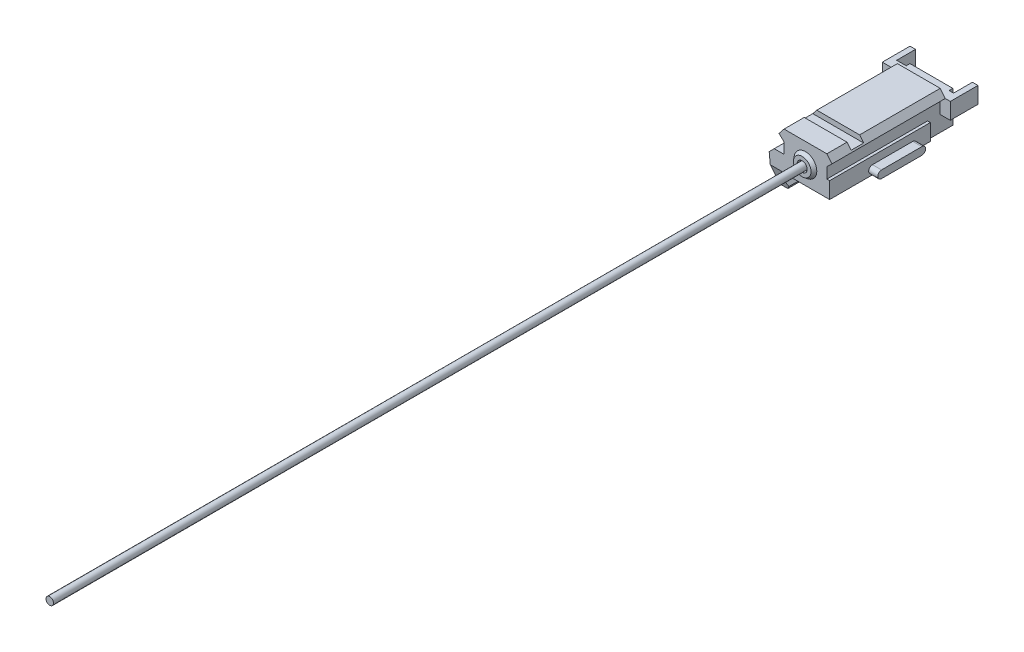
SolidWorks part; units mm, degrees
ref_plane "Plan de face" through (0, 0, 0) normal (0, 0, 1) x (1, 0, 0)
ref_plane "Plan de dessus" through (0, 0, 0) normal (0, 1, 0) x (1, 0, 0)
ref_plane "Plan de droite" through (0, 0, 0) normal (1, 0, 0) x (0, 0, -1)
sketch "Esquisse1" plane through (0, 0, 0) normal (0, 0, 1) x (1, 0, 0)
  line L0 (0, -2) -> (2, 0)
  line L1 (2, 0) -> (4.8, 0)
  line L3 (1.23, -14) -> (4.43, -14)
  line L4 (4.8, 0) -> (4.8, -10.6)
  line L6 (4.43, -11) -> (5.42, -12.5)
  line L7 (5.42, -12.5) -> (4.43, -14)
  line L8 (0, -2) -> (1.23, -14)
  line L9 (4.43, -11) -> (4.8, -10.6)
  point P0 (0, 0)
  dimension "D1" = 4.8
  dimension "D2" = 3.2
  dimension "D6" = 12
  dimension "D5" = 2
  dimension "D3" = 4.19
  dimension "D4" = 2.8
  dimension "D7" = 1.5
  dimension "D8" = 3
  dimension "D9" = 10.6
extrude "Boss.-Extru.1" add sketch "Esquisse1" along normal blind 40
sketch "Esquisse2" plane through (4.8, 0, 0) normal (1, 0, 0) x (0, 0, -1)
  line L1 (-37, -14) -> (-40, -6.3)
  line L2 (-40, -6.3) -> (-40, -14)
  line L3 (-40, -14) -> (0, -14) construction
  line L4 (-40, -14) -> (-37, -14)
  line L5 (-40, 0) -> (0, 0) construction
  line L6 (-40, -10.6) -> (-40, 0) construction
  dimension "D1" = 6.3
  dimension "D2" = 3
extrude "Enlèv. mat.-Extru.1" cut sketch "Esquisse2" against normal through all and the other way through all
ref_plane "Plan1" through (0, -6.5, 0) normal (0, 1, 0) x (-1, 0, 0)
sketch "Esquisse3" plane through (0, -6.5, 0) normal (0, 1, 0) x (-1, 0, 0)
  line L1 (-5.7068, 0) -> (-1.3, 0)
  line L2 (-4.8, 0) -> (-2, 0) construction
  line L3 (-5.7068, 0) -> (-5.7068, 3.75)
  line L4 (-1.3, 0) -> (-4.8, 3.75)
  line L5 (-4.8, 3.75) -> (-5.7068, 3.75)
  line L6 (-4.8, 40) -> (-4.8, 0) construction
  dimension "D1" = 3.5
  dimension "D2" = 3.75
extrude "Enlèv. mat.-Extru.3" cut sketch "Esquisse3" against normal blind 40
ref_plane "Plan2" through (-0.2, 0, 0) normal (1, 0, 0) x (0, 0, -1)
hole_wizard "Chambrage pour vis à tête hexagonale M31" positions "Esquisse5" profile "Esquisse4" counterbore size "M3" standard "ISO" end condition through all
sketch "Esquisse5" plane through (-0.2, 2.2587, 74.5722) normal (1, 0, 0) x (0, 0, -1)
  line L1 (34.5722, -2.2587) -> (74.5722, -2.2587) construction
  line L2 (34.5722, -8.5587) -> (34.5722, -2.2587) construction
  point P0 (55.5722, -11.2587)
  point P1 (45.5722, -11.2587)
  dimension "D1" = 10
  dimension "D2" = 11
  dimension "D3" = 9
sketch "Esquisse4" plane through (-0.2, -9, 19) normal (0, 1, 0) x (0, 0, 1)
  line L0 (0, 0) -> (0, 5.62)
  line L1 (0, 5.62) -> (1.7, 5.62)
  line L3 (1.7, 5.62) -> (1.7, 3)
  line L4 (1.7, 3) -> (2.1, 3)
  line L5 (2.1, 3) -> (2.1, 0)
  line L7 (2.1, 0) -> (0, 0)
  line L11 (0, -6.35) -> (0, 107.95) construction
  dimension "Diamètre du perçage jusqu'au prochain" = 3.4
  dimension "Profondeur du perçage jusqu'au prochain" = 5.62
  dimension "Diamètre du chambrage" = 4.2
  dimension "Profondeur du chambrage" = 3
sketch "Esquisse6" plane through (0.6948, 0, -0.6485) normal (0.7311, 0, -0.6823) x (-0.6823, 0, -0.7311)
  line L1 (-10.1213, -7.9507) -> (-3.0712, -7.9507)
  line L2 (-10.1213, -7.9507) -> (-10.1213, -15.3098)
  line L3 (-10.1213, -15.3098) -> (-3.0712, -15.3098)
  line L4 (-3.0712, -7.9507) -> (-3.0712, -15.3098)
extrude "Enlèv. mat.-Extru.4" cut sketch "Esquisse6" along normal blind 10
ref_plane "Plan3" through (14.4, 0, 0) normal (1, 0, 0) x (0, 0, -1)
sketch "Esquisse7" plane through (0, 0, 40) normal (0, 0, 1) x (1, 0, 0)
  line L0 (4.8, -6.3) -> (4.8, 0) construction
  line L1 (4.8, -6.5) -> (24, -6.5)
  line L2 (4.8, -6.5) -> (4.8, 0)
  line L3 (5.9, 8.7) -> (22.9, 8.7)
  line L4 (22.9, 0) -> (24, 0)
  line L5 (1.23, -14) -> (4.43, -14) construction
  line L6 (5.9, 8.7) -> (3.9, 6.2)
  line L7 (3.9, 6.2) -> (5.9, 4.3)
  line L8 (5.9, 4.3) -> (5.9, 0)
  line L9 (5.9, 0) -> (4.8, 0)
  line L10 (4.8, 0) -> (2, 0) construction
  line L12 (14.4, -8.9588) -> (14.4, 10.2832) construction
  line L13 (14.4, -11.5346) -> (14.4, 11.5346) construction
  line L14 (22.9, 4.3) -> (22.9, 0)
  line L15 (24.9, 6.2) -> (22.9, 4.3)
  line L16 (22.9, 8.7) -> (24.9, 6.2)
  line L17 (24, -6.5) -> (24, 0)
  point P25 (14.4, 8.7)
  point P26 (14.4, -6.5)
  dimension "D1" = 7.5
  dimension "D2" = 15.2
  dimension "D3" = 17
  dimension "D4" = 2
  dimension "D5" = 4.3
  dimension "D6" = 6.2
extrude "Boss.-Extru.2" add sketch "Esquisse7" against normal blind 50
sketch "Esquisse8" plane through (14.4, 0, 0) normal (1, 0, 0) x (0, 0, -1)
  line L0 (-31.3081, 0.7) -> (-77.4972, 0.7) construction
  line L1 (-40, 5.2) -> (-41.3, 4.2)
  line L2 (-41.3, 4.2) -> (-41.3, 2.7)
  line L3 (-41.3, 2.7) -> (-40, 2.7)
  line L5 (-40, 0) -> (-40, 4.3) construction
  line L6 (-40, 2.7) -> (-40, 5.2)
  line L8 (10, 8.7) -> (-40, 8.7) construction
  dimension "D1" = 1.3
  dimension "D2" = 9
  dimension "D3" = 8
  dimension "D4" = 4
  dimension "D5" = 7
revolve "Révolution1" add sketch "Esquisse8" angle 360 about L0
sketch "Esquisse9" plane through (0, 0, 0) normal (1, 0, 0) x (0, 0, -1)
  line L0 (10, 8.7) -> (-40, 8.7) construction
  line L1 (10, 8.7) -> (5, 8.7)
  line L2 (10, 0) -> (10, 4.3) construction
  line L3 (10, 6.2) -> (10, 8.7)
  line L4 (5, 8.7) -> (5, 6.2)
  line L5 (5, 6.2) -> (10, 6.2)
  dimension "D1" = 5
  dimension "D2" = 2.5
extrude "Enlèv. mat.-Extru.5" cut sketch "Esquisse9" along normal through all
sketch "Esquisse11" plane through (0, 0, 0) normal (0, 1, 0) x (1, 0, 0)
  line L0 (24.9, 10) -> (24.9, 5) construction
  line L1 (24.9, 10) -> (24.9, 5)
  line L2 (24.9, 5) -> (3.9, 5) construction
  line L3 (24.9, 5) -> (22.9, 5)
  line L5 (3.657, 10) -> (3.657, 5)
  line L6 (22.9, 10) -> (24.9, 10) construction
  line L7 (22.9, 10) -> (24.9, 10)
  line L8 (22.9, 10) -> (22.9, -40) construction
  line L9 (22.9, 10) -> (22.9, 5)
  line L10 (5.9, 10) -> (4.8, 10) construction
  line L11 (5.9, 10) -> (3.657, 10)
  line L12 (5.9, 10) -> (5.9, -40) construction
  line L13 (5.9, 10) -> (5.9, 5)
  line L14 (5.9, 5) -> (3.657, 5)
extrude "Enlèv. mat.-Extru.6" cut sketch "Esquisse11" along normal blind 10
sketch "Esquisse13" plane through (5.9, 0, 0) normal (-1, 0, 0) x (0, 0, 1)
  line L0 (0, -6.5) -> (0, 0) construction
  line L1 (-10, 0) -> (0, 0)
  line L2 (-10, 0) -> (-10, -6.5)
  line L3 (-10, -6.5) -> (0, -6.5)
  line L4 (0, 0) -> (0, -6.5)
  line L5 (-10, -6.5) -> (0, -6.5) construction
extrude "Enlèv. mat.-Extru.7" cut sketch "Esquisse13" along normal blind 6.5
sketch "Esquisse14" plane through (22.9, 0, 0) normal (1, 0, 0) x (0, 0, -1)
  line L0 (10, -6.5) -> (-40, -6.5) construction
  line L1 (10, 0) -> (0, 0)
  line L2 (10, 0) -> (10, -6.5)
  line L3 (10, -6.5) -> (0, -6.5)
  line L4 (0, 0) -> (0, -6.5)
  line L5 (0, -6.5) -> (0, 0) construction
extrude "Enlèv. mat.-Extru.8" cut sketch "Esquisse14" along normal blind 6.5
sketch "Esquisse10" plane through (0, 6.2, 0) normal (0, 1, 0) x (1, 0, 0)
  line L0 (22.9, 5) -> (5.9, 5) construction
  line L1 (26.9, 5) -> (-0.1, 5)
  line L2 (-0.1, 5) -> (-0.1, 16)
  line L3 (-0.1, 16) -> (2.1, 16)
  line L4 (2.1, 16) -> (2.1, 8.5)
  line L5 (2.1, 8.5) -> (24.7, 8.5)
  line L6 (24.7, 8.5) -> (24.7, 16)
  line L7 (24.7, 16) -> (26.9, 16)
  line L8 (26.9, 16) -> (26.9, 5)
  line L10 (22.9, 5) -> (22.9, 10) construction
  dimension "D1" = 27
  dimension "D2" = 2.2
  dimension "D3" = 2.2
  dimension "D4" = 11
  dimension "D5" = 3.5
  dimension "D6" = 1.8
extrude "Boss.-Extru.3" add sketch "Esquisse10" against normal blind 6.5
ref_plane "Plan4" through (0, 0, 32) normal (0, 0, 1) x (1, 0, 0)
sketch "Esquisse15" plane through (0, 0, 32) normal (0, 0, 1) x (1, 0, 0)
  line L0 (22.9, 8.7) -> (5.9, 8.7) construction
  line L1 (24.9, 8.7) -> (3.9, 8.7)
  line L2 (24.9, 8.7) -> (24.9, 6.7)
  line L3 (24.9, 6.7) -> (3.9, 6.7)
  line L4 (3.9, 8.7) -> (3.9, 6.7)
  dimension "D1" = 2
extrude "Enlèv. mat.-Extru.9" cut sketch "Esquisse15" against normal blind 5
sketch "Esquisse16" plane through (24, 0, 0) normal (1, 0, 0) x (0, 0, -1)
  line L0 (-7, -6) -> (-23, -6) construction
  line L1 (-23, -3) -> (-7, -3) construction
  line L2 (-7, -6) -> (-23, -6)
  line L3 (-23, -3) -> (-7, -3)
  arc A0 (-7, -6) -> (-7, -3) centre (-7, -4.5) ccw construction
  arc A1 (-23, -3) -> (-23, -6) centre (-23, -4.5) ccw construction
  arc A2 (-7, -6) -> (-7, -3) centre (-7, -4.5) ccw
  arc A3 (-23, -3) -> (-23, -6) centre (-23, -4.5) ccw
extrude "Boss.-Extru.4" add sketch "Esquisse16" along normal up to vertex (3.6 mm away)
ref_plane "Plan5" through (0, -12.5, 0) normal (0, -1, 0) x (1, 0, 0)
sketch "Esquisse17" plane through (0, 0, 40) normal (0, 0, 1) x (1, 0, 0)
  circle A2 centre (14.4, 0.7) radius 1.5
  circle A3 centre (14.4, 0.7) radius 1.5
  dimension "D1" = 0.5
extrude "Boss.-Extru.5" add sketch "Esquisse17" along normal blind 300
